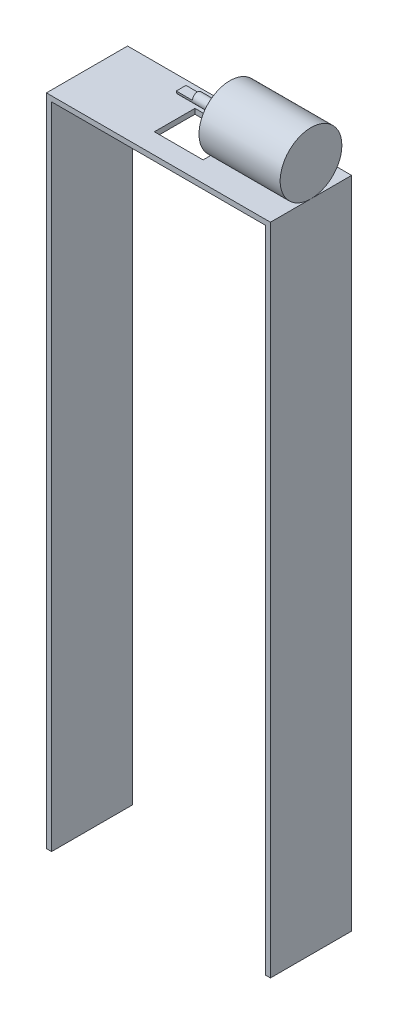
SolidWorks part; units mm, degrees
ref_plane "Front Plane" through (0, 0, 0) normal (0, 0, 1) x (1, 0, 0)
ref_plane "Top Plane" through (0, 0, 0) normal (0, 1, 0) x (1, 0, 0)
ref_plane "Right Plane" through (0, 0, 0) normal (1, 0, 0) x (0, 0, -1)
sketch "Sketch2" plane through (0, 0, 0) normal (0, 1, 0) x (1, 0, 0)
  line L0 (3.175, 50) -> (0, 50)
  line L1 (3.175, 50) -> (3.175, 0)
  line L2 (3.175, 0) -> (0, 0)
  line L3 (0, 50) -> (0, 0)
  line L4 (138, 50) -> (134.825, 50)
  line L5 (138, 50) -> (138, 0)
  line L6 (138, 0) -> (134.825, 0)
  line L7 (134.825, 50) -> (134.825, 0)
  dimension "D1" = 50
  dimension "D2" = 3.175
  dimension "D3" = 131.65
extrude "Boss-Extrude1" add sketch "Sketch2" along normal blind 400
sketch "Sketch3" plane through (0, 400, 0) normal (0, 1, 0) x (1, 0, 0)
  line L1 (0, 50) -> (138, 50)
  line L2 (0, 50) -> (0, 0)
  line L3 (0, 0) -> (138, 0)
  line L4 (138, 50) -> (138, 0)
extrude "Boss-Extrude2" add sketch "Sketch3" along normal blind 3.175
sketch "Sketch4" plane through (0, 403.175, 0) normal (0, 1, 0) x (1, 0, 0)
  line L0 (0, 12.5) -> (54, 12.5) construction
  line L1 (0, 50) -> (0, 0) construction
  line L2 (138, 0) -> (138, 50) construction
  line L3 (84, 37.5) -> (84, 50) construction
  line L5 (54, 12.5) -> (54, 37.5)
  line L6 (54, 37.5) -> (84, 37.5)
  line L7 (84, 12.5) -> (84, 37.5)
  line L8 (138, 50) -> (0, 50) construction
  line L9 (84, 12.5) -> (84, 0) construction
  line L10 (0, 0) -> (138, 0) construction
  line L11 (84, 12.5) -> (138, 12.5) construction
  line L12 (54, 12.5) -> (84, 12.5)
  point P11 (54, 12.5)
  point P19 (84, 12.5)
  dimension "D1" = 30
  dimension "D2" = 25
extrude "Cut-Extrude1" cut sketch "Sketch4" against normal up to next
sketch "Sketch5" plane through (138, 0, 0) normal (1, 0, 0) x (0, 0, -1)
  line L0 (0, 403.175) -> (50, 403.175) construction
  circle A0 centre (25, 422.175) radius 19
  dimension "D1" = 38
extrude "Boss-Extrude3" add sketch "Sketch5" against normal blind 50 separate body
sketch "Sketch6" plane through (88, 0, 0) normal (-1, 0, 0) x (0, 0, 1)
  line L0 (-25, 441.175) -> (-25, 403.175) construction
  circle A0 centre (-25, 422.175) radius 19 construction
  circle A1 centre (-25, 422.175) radius 3
  dimension "D1" = 6
extrude "Boss-Extrude4" add sketch "Sketch6" along normal blind 30
sketch "Sketch7" plane through (58, 0, 0) normal (-1, 0, 0) x (0, 0, 1)
  line L0 (-28, 422.175) -> (-22, 422.175) construction
  line L1 (-28, 422.175) -> (-22, 422.175)
  line L2 (-28, 422.175) -> (-28, 425.175)
  line L3 (-28, 425.175) -> (-22, 425.175)
  line L4 (-22, 422.175) -> (-22, 425.175)
  circle A0 centre (-25, 422.175) radius 3 construction
  circle A1 centre (-25, 422.175) radius 3 construction
  point P3 (-25, 425.175)
  dimension "D1" = 6
extrude "Cut-Extrude2" cut sketch "Sketch7" against normal blind 10
